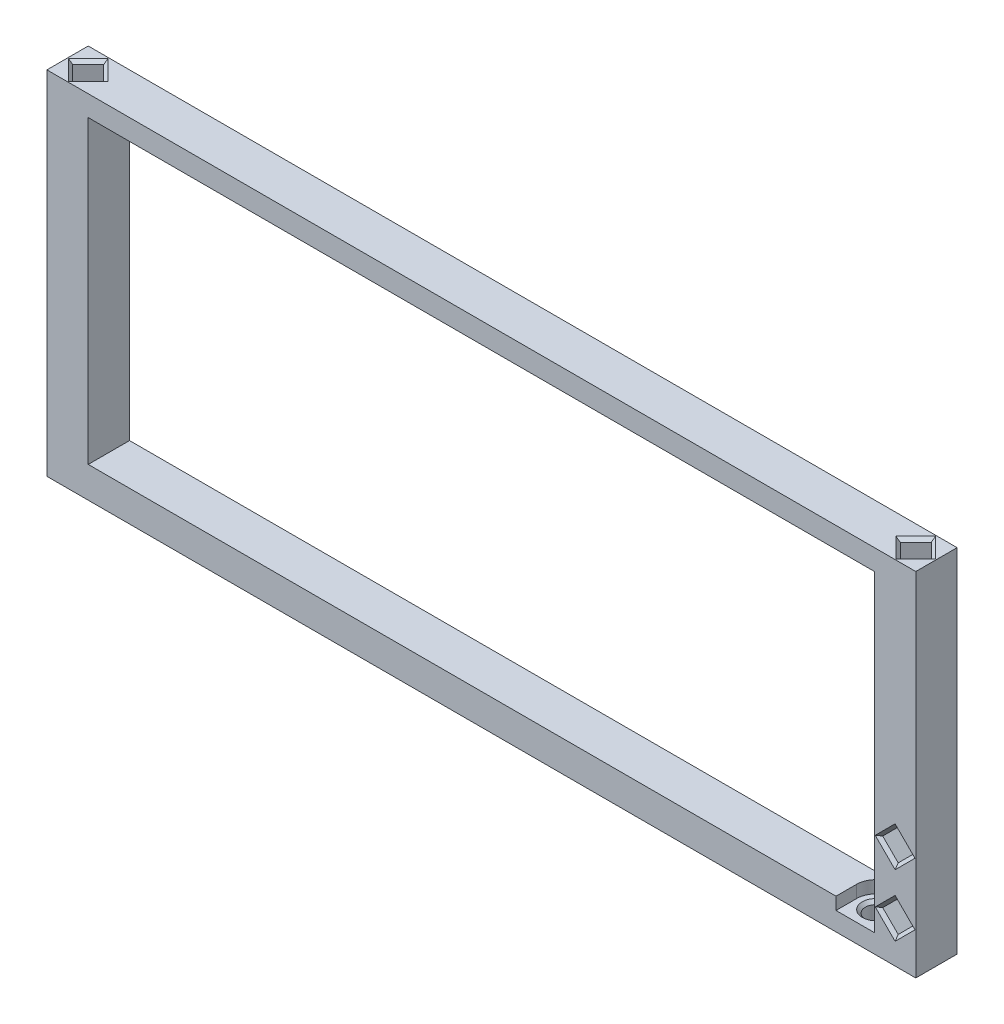
SolidWorks part; units mm, degrees
ref_plane "Front Plane" through (0, 0, 0) normal (0, 0, 1) x (1, 0, 0)
ref_plane "Top Plane" through (0, 0, 0) normal (0, 1, 0) x (1, 0, 0)
ref_plane "Right Plane" through (0, 0, 0) normal (1, 0, 0) x (0, 0, -1)
sketch "Sketch1" plane through (0, 0, 0) normal (0, 0, 1) x (1, 0, 0)
  line L1 (-89.0005, 36.06) -> (89.0005, 36.06)
  line L2 (-89.0005, 36.06) -> (-89.0005, -36.06)
  line L3 (-89.0005, -36.06) -> (89.0005, -36.06)
  line L4 (89.0005, 36.06) -> (89.0005, -36.06)
  line L5 (-80.5338, 31.8267) -> (80.5338, 31.8267)
  line L6 (-80.5338, 31.8267) -> (-80.5338, -29.71)
  line L7 (-80.5338, -29.71) -> (80.5338, -29.71)
  line L8 (80.5338, 31.8267) -> (80.5338, -29.71)
  point P8 (0, 36.06)
  point P10 (0, 31.8267)
  point P12 (-89.0005, 0)
  dimension "D1" = 178.001
  dimension "D2" = 4.2333
  dimension "D3" = 8.4667
  dimension "D4" = 72.12
  dimension "D5" = 6.35
extrude "Boss-Extrude1" add sketch "Sketch1" along normal blind 8.4667
sketch "Sketch2" plane through (0, 36.06, 0) normal (0, 1, 0) x (1, 0, 0)
  line L0 (-87.9422, -4.2333) -> (-84.7672, -1.0583)
  line L1 (-87.9422, -4.2333) -> (-84.7672, -7.4083)
  line L2 (-84.7672, -1.0583) -> (-81.5922, -4.2333)
  line L3 (-84.7672, -7.4083) -> (-81.5922, -4.2333)
  line L4 (-87.9422, -4.2333) -> (-81.5922, -4.2333) construction
  line L5 (-84.7672, -1.0583) -> (-84.7672, -7.4083) construction
  line L6 (81.5922, -4.2333) -> (84.7672, -1.0583)
  line L7 (81.5922, -4.2333) -> (84.7672, -7.4083)
  line L8 (84.7672, -1.0583) -> (87.9422, -4.2333)
  line L9 (84.7672, -7.4083) -> (87.9422, -4.2333)
  line L10 (81.5922, -4.2333) -> (87.9422, -4.2333) construction
  line L11 (84.7672, -1.0583) -> (84.7672, -7.4083) construction
  line L12 (89.0005, -8.4667) -> (-89.0005, -8.4667) construction
  line L13 (-89.0005, -8.4667) -> (-89.0005, 0) construction
  line L14 (89.0005, -8.4667) -> (89.0005, 0) construction
  point P1 (-84.7672, -4.2333)
  point P2 (84.7672, -4.2333)
  dimension "D1" = 6.35
  dimension "D2" = 4.2333
  dimension "D3" = 4.2333
  dimension "D4" = 4.2333
extrude "Cut-Extrude1" cut sketch "Sketch2" against normal blind 5.08
sketch "Sketch3" plane through (0, 0, 8.4667) normal (0, 0, 1) x (1, 0, 0)
  line L0 (81.5922, -27.5933) -> (84.7672, -24.4183)
  line L1 (81.5922, -27.5933) -> (84.7672, -30.7683)
  line L2 (84.7672, -24.4183) -> (87.9422, -27.5933)
  line L3 (84.7672, -30.7683) -> (87.9422, -27.5933)
  line L4 (81.5922, -27.5933) -> (87.9422, -27.5933) construction
  line L5 (84.7672, -24.4183) -> (84.7672, -30.7683) construction
  line L6 (-89.0005, -36.06) -> (89.0005, -36.06) construction
  line L7 (89.0005, -36.06) -> (89.0005, 36.06) construction
  line L8 (84.7672, -11.7183) -> (87.9422, -14.8933)
  line L9 (84.7672, -11.7183) -> (81.5922, -14.8933)
  line L10 (87.9422, -14.8933) -> (84.7672, -18.0683)
  line L11 (81.5922, -14.8933) -> (84.7672, -18.0683)
  line L12 (84.7672, -11.7183) -> (84.7672, -18.0683) construction
  line L13 (87.9422, -14.8933) -> (81.5922, -14.8933) construction
  point P1 (84.7672, -27.5933)
  point P10 (84.7672, -14.8933)
  dimension "D1" = 6.35
  dimension "D2" = 8.4667
  dimension "D3" = 4.2333
  dimension "D4" = 12.7
extrude "Cut-Extrude2" cut sketch "Sketch3" against normal blind 5.08
sketch "Sketch4" plane through (-89.0005, 0, 0) normal (-1, 0, 0) x (0, 0, 1)
  line L0 (1.0583, 27.5933) -> (4.2333, 30.7683)
  line L1 (1.0583, 27.5933) -> (4.2333, 24.4183)
  line L2 (4.2333, 30.7683) -> (7.4083, 27.5933)
  line L3 (4.2333, 24.4183) -> (7.4083, 27.5933)
  line L4 (1.0583, 27.5933) -> (7.4083, 27.5933) construction
  line L5 (4.2333, 30.7683) -> (4.2333, 24.4183) construction
  line L6 (1.0583, -27.5933) -> (4.2333, -24.4183)
  line L7 (1.0583, -27.5933) -> (4.2333, -30.7683)
  line L8 (4.2333, -24.4183) -> (7.4083, -27.5933)
  line L9 (4.2333, -30.7683) -> (7.4083, -27.5933)
  line L10 (1.0583, -27.5933) -> (7.4083, -27.5933) construction
  line L11 (4.2333, -24.4183) -> (4.2333, -30.7683) construction
  line L12 (8.4667, 36.06) -> (0, 36.06) construction
  line L13 (0, 36.06) -> (0, -36.06) construction
  line L14 (8.4667, -36.06) -> (0, -36.06) construction
  point P1 (4.2333, 27.5933)
  point P2 (4.2333, -27.5933)
  dimension "D1" = 8.4667
  dimension "D2" = 4.2333
  dimension "D3" = 8.4667
  dimension "D4" = 6.35
extrude "Cut-Extrude3" cut sketch "Sketch4" against normal blind 5.08
sketch "Sketch5" plane through (0, -36.06, 0) normal (0, -1, 0) x (1, 0, 0)
  line L0 (81.5922, 4.2333) -> (84.7672, 7.4083)
  line L1 (81.5922, 4.2333) -> (84.7672, 1.0583)
  line L2 (84.7672, 7.4083) -> (87.9422, 4.2333)
  line L3 (84.7672, 1.0583) -> (87.9422, 4.2333)
  line L4 (81.5922, 4.2333) -> (87.9422, 4.2333) construction
  line L5 (84.7672, 7.4083) -> (84.7672, 1.0583) construction
  line L6 (89.0005, 8.4667) -> (89.0005, 0) construction
  line L7 (-89.0005, 8.4667) -> (89.0005, 8.4667) construction
  point P1 (84.7672, 4.2333)
  dimension "D1" = 4.2333
  dimension "D2" = 4.2333
  dimension "D3" = 6.35
extrude "Cut-Extrude4" cut sketch "Sketch5" against normal blind 5.08
chamfer "Chamfer1" distance 0.635 angle 45 56 edges at (-86.3547, 30.98, 2.6458) (-83.1797, 30.98, 2.6458) (-83.1797, 30.98, 5.8208) (-86.3547, 30.98, 5.8208) (83.1797, 30.98, 2.6458) (86.3547, 30.98, 2.6458) (86.3547, 30.98, 5.8208) (83.1797, 30.98, 5.8208) (-83.1797, 36.06, 2.6458) (-83.1797, 36.06, 5.8208) (-86.3547, 36.06, 5.8208) (-86.3547, 36.06, 2.6458) (86.3547, 36.06, 5.8208) (86.3547, 36.06, 2.6458) (83.1797, 36.06, 5.8208) (83.1797, 36.06, 2.6458) (83.1797, -26.0058, 3.3867) (86.3547, -26.0058, 3.3867) (86.3547, -29.1808, 3.3867) (83.1797, -29.1808, 3.3867) (83.1797, -29.1808, 8.4667) (86.3547, -29.1808, 8.4667) (86.3547, -26.0058, 8.4667) (83.1797, -26.0058, 8.4667) (-83.9205, -26.0058, 2.6458) (-83.9205, -26.0058, 5.8208) (-83.9205, -29.1808, 5.8208) (-83.9205, -29.1808, 2.6458) (-83.9205, 29.1808, 2.6458) (-83.9205, 29.1808, 5.8208) (-83.9205, 26.0058, 5.8208) (-83.9205, 26.0058, 2.6458) (-89.0005, -29.1808, 2.6458) (-89.0005, -29.1808, 5.8208) (-89.0005, -26.0058, 5.8208) (-89.0005, -26.0058, 2.6458) (-89.0005, 26.0058, 2.6458) (-89.0005, 26.0058, 5.8208) (-89.0005, 29.1808, 5.8208) (-89.0005, 29.1808, 2.6458) (86.3547, -13.3058, 3.3867) (86.3547, -16.4808, 3.3867) (83.1797, -16.4808, 3.3867) (83.1797, -13.3058, 3.3867) (83.1797, -16.4808, 8.4667) (86.3547, -16.4808, 8.4667) (86.3547, -13.3058, 8.4667) (83.1797, -13.3058, 8.4667) (83.1797, -30.98, 5.8208) (86.3547, -30.98, 5.8208) (86.3547, -30.98, 2.6458) (83.1797, -30.98, 2.6458) (86.3547, -36.06, 5.8208) (86.3547, -36.06, 2.6458) (83.1797, -36.06, 2.6458) (83.1797, -36.06, 5.8208)
sketch "Sketch6" plane through (0, -29.71, 0) normal (0, 1, 0) x (1, 0, 0)
  line L0 (72.6598, -4.2333) -> (72.6598, -8.4667)
  line L1 (-80.5338, -8.4667) -> (80.5338, -8.4667) construction
  line L2 (72.6598, -8.4667) -> (80.5338, -8.4667)
  line L3 (80.5338, -8.4667) -> (80.5338, -4.2333)
  line L4 (80.5338, -8.4667) -> (80.5338, 0) construction
  arc A0 (80.5338, -4.2333) -> (72.6598, -4.2333) centre (76.5968, -4.2333) ccw
  point P1 (79.5342, -8.4667)
  point P2 (80.5338, -8.4667)
  dimension "D1" = 3.937
  dimension "D2" = 4.2333
extrude "Cut-Extrude5" cut sketch "Sketch6" against normal blind 2.54
sketch "Sketch7" plane through (0, -32.25, 0) normal (0, 1, 0) x (1, 0, 0)
  arc A0 (80.5338, -4.2333) -> (72.6598, -4.2333) centre (76.5968, -4.2333) ccw construction
  point P0 (76.5968, -4.2333)
hole_wizard "#18 (0.1695) Diameter Hole1" positions "Sketch7" profile "Sketch8" hole size "#18" standard "ANSI Inch"
sketch "Sketch8" plane through (76.5968, -32.25, 4.2333) normal (1, 0, 0) x (0, 0, 1)
  line L0 (0, 0) -> (0, 3.81)
  line L1 (0, 3.81) -> (2.1526, 3.81)
  line L2 (2.1526, 3.81) -> (2.1526, 0.635)
  line L3 (2.1526, 0.635) -> (2.7876, 0)
  line L5 (2.7876, 0) -> (0, 0)
  line L6 (-2.1526, 0.635) -> (-2.7876, 0) construction
  line L11 (0, -6.35) -> (0, 107.95) construction
  dimension "Thru Hole Dia." = 4.3053
  dimension "Thru Hole Depth" = 3.81
  dimension "Near C'Sink Dia." = 5.5753
  dimension "Near C'Sink Angle" = 90
